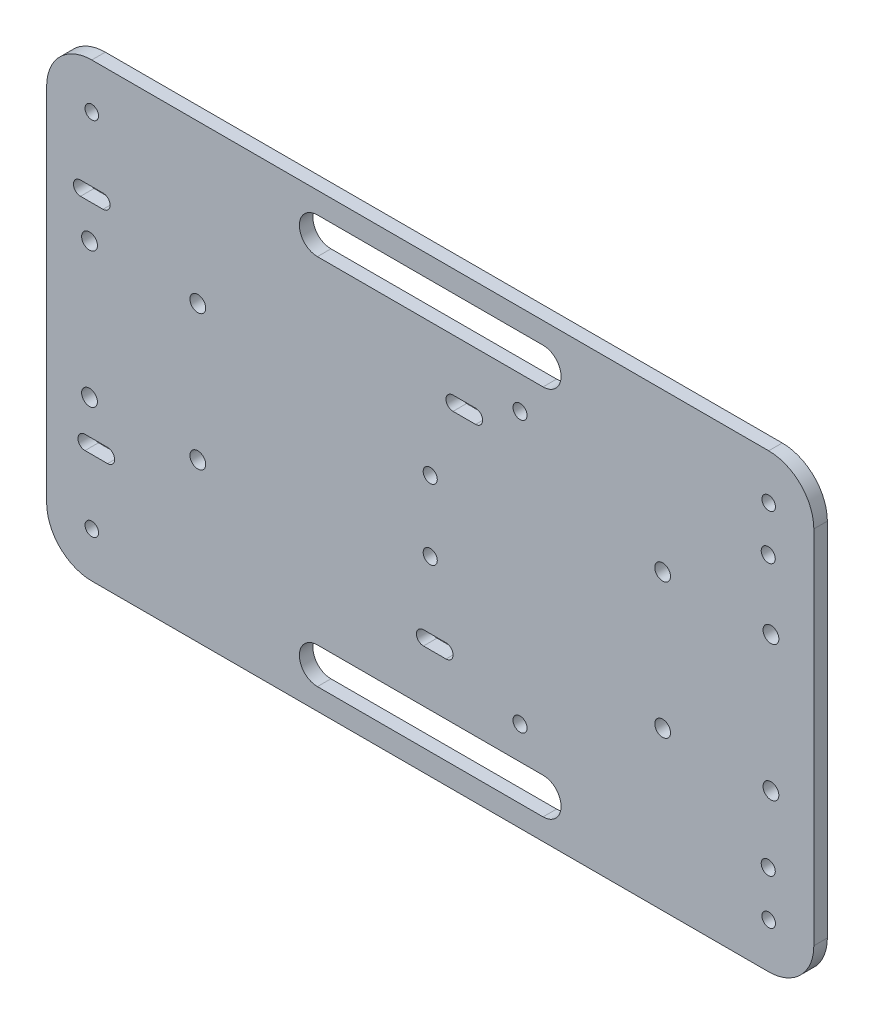
SolidWorks part; units mm, degrees
ref_plane "Front Plane" through (0, 0, 0) normal (0, 0, 1) x (1, 0, 0)
ref_plane "Top Plane" through (0, 0, 0) normal (0, 1, 0) x (1, 0, 0)
ref_plane "Right Plane" through (0, 0, 0) normal (1, 0, 0) x (0, 0, -1)
sketch "Sketch1" plane through (0, 0, 0) normal (0, 0, 1) x (1, 0, 0)
  line L0 (-85, 0) -> (85, 0) construction
  line L1 (-75, 50) -> (75, 50)
  line L2 (-85, 40) -> (-85, -40)
  line L3 (-75, -50) -> (75, -50)
  line L4 (85, 40) -> (85, -40)
  line L5 (-85, 50) -> (85, -50) construction
  line L6 (-85, -50) -> (85, 50) construction
  line L7 (0, 50) -> (0, -50) construction
  line L8 (-25, 41.2578) -> (25, 41.2578) construction
  line L9 (-25, 45.2578) -> (25, 45.2578)
  line L10 (-25, 37.2578) -> (25, 37.2578)
  line L11 (-25, -41.2578) -> (25, -41.2578) construction
  line L12 (-25, -45.2578) -> (25, -45.2578)
  line L13 (-25, -37.2578) -> (25, -37.2578)
  line L14 (-72.5, 24.15) -> (-77.5, 24.15) construction
  line L17 (-72.5, 22.59) -> (-77.5, 22.59)
  line L18 (-72.5, 25.71) -> (-77.5, 25.71)
  line L21 (10.05, 24.15) -> (5.05, 24.15) construction
  line L24 (10.05, 22.59) -> (5.05, 22.59)
  line L27 (10.05, 25.71) -> (5.05, 25.71)
  line L30 (3.5, -24.15) -> (-1.5, -24.15) construction
  line L31 (3.5, -25.71) -> (-1.5, -25.71)
  line L34 (3.5, -22.59) -> (-1.5, -22.59)
  line L39 (63.5, 20) -> (63.5, -20) construction
  line L44 (19.9, -30) -> (74.9, -30) construction
  line L45 (19.9, -30) -> (19.9, 30) construction
  line L48 (-71.5, -24.15) -> (-76.5, -24.15) construction
  line L49 (-71.5, -25.71) -> (-76.5, -25.71)
  line L50 (-71.5, -22.59) -> (-76.5, -22.59)
  line L51 (19.9, 30) -> (74.9, 30) construction
  line L56 (74.9, -30) -> (74.9, 30) construction
  line L57 (19.9, -30) -> (74.9, 30) construction
  line L58 (19.9, 30) -> (74.9, -30) construction
  line L62 (85, 20) -> (85, -20)
  line L63 (85, 20) -> (42, 20) construction
  line L64 (85, 20) -> (85, -20) construction
  line L65 (85, -20) -> (42, -20) construction
  line L66 (42, 20) -> (42, -20) construction
  line L67 (85, 20) -> (42, -20) construction
  line L68 (85, -20) -> (42, 20) construction
  line L69 (-85, -20) -> (-42, -20) construction
  line L70 (-42, 20) -> (-42, -20) construction
  line L71 (-85, 20) -> (-42, 20) construction
  line L72 (-85, 20) -> (-85, -20) construction
  arc A0 (-25, 45.2578) -> (-25, 37.2578) centre (-25, 41.2578) ccw
  arc A1 (25, 37.2578) -> (25, 45.2578) centre (25, 41.2578) ccw
  arc A2 (-25, -45.2578) -> (-25, -37.2578) centre (-25, -41.2578) cw
  arc A3 (25, -37.2578) -> (25, -45.2578) centre (25, -41.2578) cw
  arc A20 (75, 50) -> (85, 40) centre (75, 40) cw
  arc A21 (85, -40) -> (75, -50) centre (75, -40) cw
  arc A22 (-75, -50) -> (-85, -40) centre (-75, -40) cw
  arc A23 (-75, 50) -> (-85, 40) centre (-75, 40) ccw
  circle A24 centre (-75, 40) radius 1.5
  circle A25 centre (-75, -40) radius 1.5
  circle A26 centre (75, -40) radius 1.5
  circle A27 centre (75, 40) radius 1.5
  circle A34 centre (0, 7.78) radius 1.56
  circle A35 centre (0, -7.78) radius 1.56
  circle A36 centre (-75, 24.15) radius 1.56
  circle A37 centre (7.55, 24.15) radius 1.56
  arc A38 (-72.5, 22.59) -> (-72.5, 25.71) centre (-72.5, 24.15) ccw
  arc A39 (-77.5, 25.71) -> (-77.5, 22.59) centre (-77.5, 24.15) ccw
  arc A40 (10.05, 22.59) -> (10.05, 25.71) centre (10.05, 24.15) ccw
  arc A41 (5.05, 25.71) -> (5.05, 22.59) centre (5.05, 24.15) ccw
  circle A42 centre (-74, -24.15) radius 1.56
  circle A43 centre (1, -24.15) radius 1.56
  arc A44 (3.5, -25.71) -> (3.5, -22.59) centre (3.5, -24.15) ccw
  arc A45 (-1.5, -22.59) -> (-1.5, -25.71) centre (-1.5, -24.15) ccw
  arc A46 (-71.5, -25.71) -> (-71.5, -22.59) centre (-71.5, -24.15) ccw
  arc A47 (-76.5, -22.59) -> (-76.5, -25.71) centre (-76.5, -24.15) ccw
  circle A52 centre (74.9, -30) radius 1.56
  circle A53 centre (74.9, 30) radius 1.56
  circle A54 centre (19.9, 30) radius 1.56
  circle A55 centre (19.9, -30) radius 1.56
  circle A57 centre (75.5, 15) radius 1.75
  circle A58 centre (75.5, -15) radius 1.75
  circle A59 centre (51.5, -15) radius 1.75
  circle A60 centre (51.5, 15) radius 1.75
  circle A61 centre (-75.5, 15) radius 1.75
  circle A62 centre (-75.5, -15) radius 1.75
  circle A63 centre (-51.5, -15) radius 1.75
  circle A64 centre (-51.5, 15) radius 1.75
  point P0 (0, 0)
  point P12 (0, 41.2578)
  point P19 (0, -41.2578)
  point P30 (-75, 24.15)
  point P40 (7.55, 24.15)
  point P52 (1, -24.15)
  point P59 (-74, -24.15)
  point P64 (47.5, 0)
  point P65 (47.4, 0)
  point P73 (65, 20)
  point P75 (63.5, 0)
  dimension "D3" = 4
  dimension "D11" = 5
  dimension "D14" = 5
  dimension "D17" = 3.12
  dimension "D18" = 0
  dimension "D21" = 1.56
  dimension "D16" = 15.56
  dimension "D28" = 37.6
  dimension "D31" = 10
  dimension "D32" = 3
  dimension "D6" = 82.55
  dimension "D7" = 3.12
  dimension "D8" = 1.56
  dimension "D9" = 5
  dimension "D20" = 5
  dimension "D10" = 1.56
  dimension "D12" = 3.12
  dimension "D15" = 1.56
  dimension "D24" = 55
  dimension "D25" = 60
  dimension "D29" = 3.12
  dimension "D40" = 40
  dimension "D30" = 63.5
  dimension "D41" = 3.5
  dimension "D1" = 170
  dimension "D2" = 100
  dimension "D4" = 50
  dimension "D5" = 41.2578
  dimension "D13" = 11
  dimension "D19" = 7.78
  dimension "D22" = 75
  dimension "D23" = 24.15
  dimension "D26" = 20
  dimension "D27" = 20
  dimension "D33" = 80
  dimension "D34" = 40
  dimension "D35" = 150
  dimension "D36" = 150
  dimension "D37" = 75
  dimension "D38" = 24.15
  dimension "D39" = 43
  dimension "D42" = 12
  dimension "D43" = 15
extrude "Boss-Extrude1" add sketch "Sketch1" along normal blind 3 contours L1 A23 L2 A22 L3 A21 L4 A20 A64 A61 A58 A57 A55 A54 A53 A52 A47 L50 A46 L49 A45 L34 A44 L31 A41 L27 A40 L24 A39 L18
